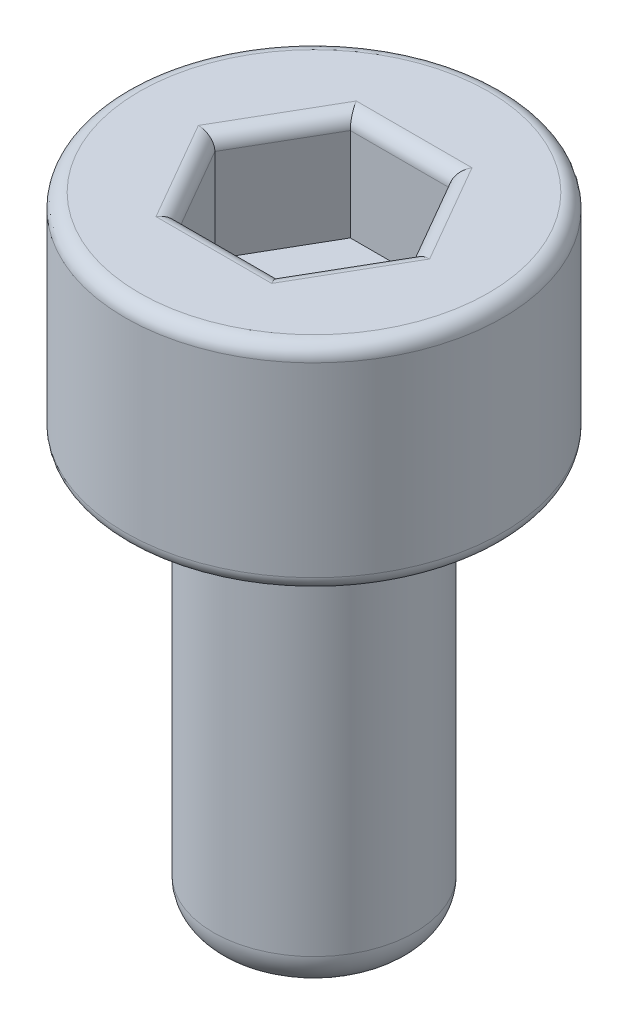
SolidWorks part; units mm, degrees
ref_plane "Front Plane" through (0, 0, 0) normal (0, 0, 1) x (1, 0, 0)
ref_plane "Top Plane" through (0, 0, 0) normal (0, 1, 0) x (1, 0, 0)
ref_plane "Right Plane" through (0, 0, 0) normal (1, 0, 0) x (0, 0, -1)
sketch "Sketch1" plane through (0, 0, 0) normal (0, 1, 0) x (1, 0, 0)
  circle A0 centre (0, 0) radius 2.64
  dimension "D1" = 5.28
extrude "Boss-Extrude1" add sketch "Sketch1" along normal blind 3
sketch "Sketch2" plane through (0, 0, 0) normal (0, -1, 0) x (1, 0, 0)
  circle A0 centre (0, 0) radius 1.405
  dimension "D1" = 2.81
extrude "Boss-Extrude2" add sketch "Sketch2" along normal blind 5.76
fillet "Fillet1" radius 0.2 2 edges at (0, 3, 2.64) (0, 0, 2.64)
sketch "Sketch3" plane through (0, 3, 0) normal (0, 1, 0) x (1, 0, 0)
  line L1 (1.3856, 0) -> (0.6928, 1.2)
  line L2 (0.6928, 1.2) -> (-0.6928, 1.2)
  line L3 (-0.6928, 1.2) -> (-1.3856, 0)
  line L4 (-1.3856, 0) -> (-0.6928, -1.2)
  line L5 (-0.6928, -1.2) -> (0.6928, -1.2)
  line L6 (0.6928, -1.2) -> (1.3856, 0)
  circle A0 centre (0, 0) radius 1.2 construction
  dimension "D1" = 2.4
extrude "Cut-Extrude1" cut sketch "Sketch3" against normal blind 1.5
fillet "Fillet2" radius 0.2 6 edges at (1.0392, 3, -0.6) (0, 3, -1.2) (-1.0392, 3, -0.6) (-1.0392, 3, 0.6) (0, 3, 1.2) (1.0392, 3, 0.6)
fillet "Fillet3" radius 0.5 1 edges at (0, -5.76, -1.405)
